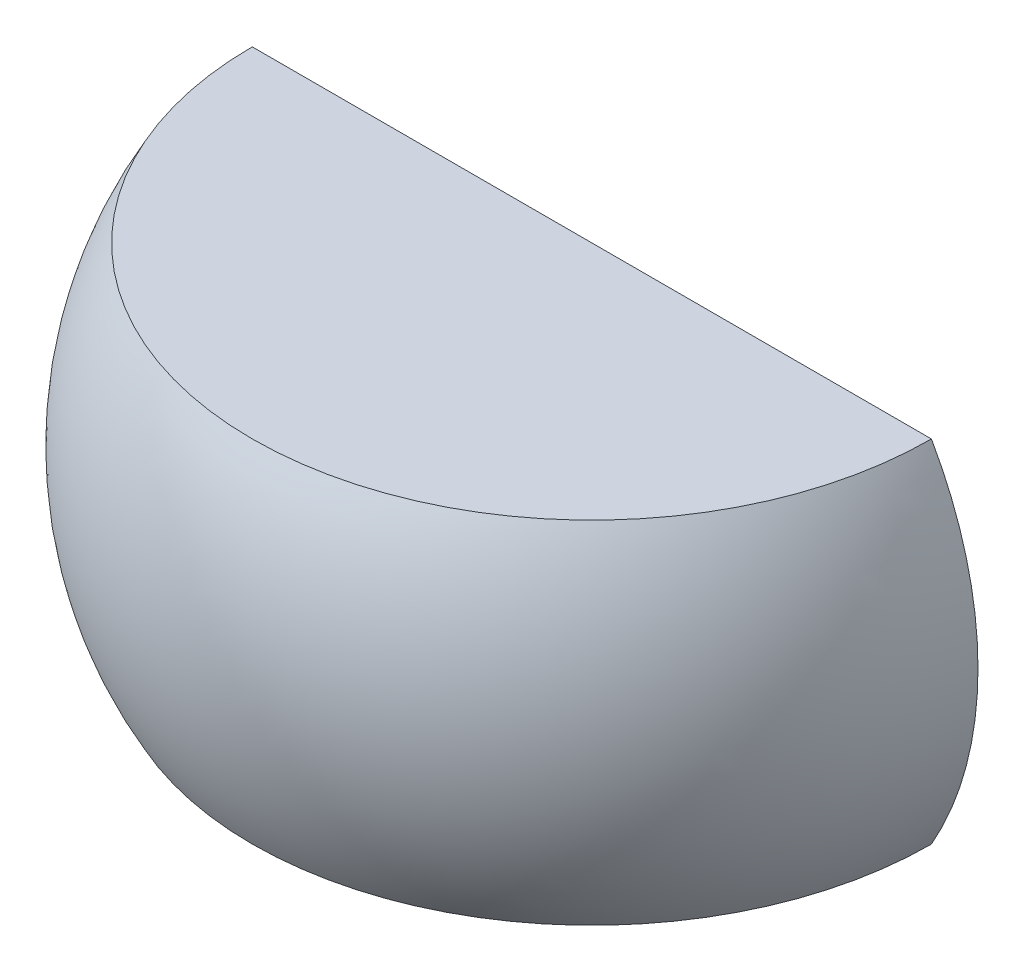
SolidWorks part; units mm, degrees
ref_plane "Alzado" through (0, 0, 0) normal (0, 0, 1) x (1, 0, 0)
ref_plane "Planta" through (0, 0, 0) normal (0, 1, 0) x (1, 0, 0)
ref_plane "Vista lateral" through (0, 0, 0) normal (1, 0, 0) x (0, 0, -1)
sketch "Croquis1" plane through (0, 0, 0) normal (0, 0, 1) x (1, 0, 0)
  line L0 (-51.7822, -4.3826) -> (-31.5822, -4.3826)
  line L1 (-51.7822, 17.4162) -> (-29.2822, 17.4162)
  line L2 (-53.2822, -5.8826) -> (-43.2485, -5.8826)
  line L3 (-31.5822, -4.3826) -> (-31.5822, -19.9667)
  line L5 (-36.7985, -13.9562) -> (-31.5822, -19.9667)
  line L6 (-43.2485, -5.8826) -> (-36.7985, -5.8826)
  line L8 (-36.7985, -5.8826) -> (-36.7985, -13.9562)
  line L9 (-29.2822, 18.9162) -> (-53.2822, 18.9162)
  line L10 (-29.2822, 17.4162) -> (-29.2822, 18.9162)
  arc A0 (-51.7822, 17.4162) -> (-51.7822, -4.3826) centre (-29.2832, 6.5168) ccw
  arc A1 (-53.2822, -5.8826) -> (-53.2822, 18.9162) centre (-31.5737, 6.5168) cw
  dimension "D3" = 1.5
  dimension "D4" = 25
  dimension "D2" = 22.5
  dimension "D5" = 1.5
revolve "Revolución1" add sketch "Croquis1" angle 180 about L10
sketch "Croquis2" plane through (0, 0, 0) normal (0, 0, -1) x (-1, 0, 0)
  line L0 (26.9822, -19.9667) -> (26.9822, -4.3826) construction
  line L1 (23.9822, -5.8826) -> (25.9822, -5.8826)
  line L2 (23.9822, -5.8826) -> (23.9822, -8.8826)
  line L3 (23.9822, -8.8826) -> (25.9822, -8.8826)
  line L4 (25.9822, -5.8826) -> (25.9822, -8.8826)
  line L6 (31.5822, -19.9667) -> (31.5822, -4.3826) construction
  line L11 (32.5822, -5.8826) -> (34.5822, -5.8826)
  line L12 (32.5822, -5.8826) -> (32.5822, -8.8826)
  line L13 (32.5822, -8.8826) -> (34.5822, -8.8826)
  line L14 (34.5822, -5.8826) -> (34.5822, -8.8826)
  line L15 (32.5822, -9.8826) -> (34.5822, -9.8826)
  line L16 (32.5822, -9.8826) -> (32.5822, -12.8826)
  line L17 (32.5822, -12.8826) -> (34.5822, -12.8826)
  line L18 (34.5822, -9.8826) -> (34.5822, -12.8826)
  line L19 (23.9822, -9.8826) -> (25.9822, -9.8826)
  line L20 (23.9822, -9.8826) -> (23.9822, -12.8826)
  line L21 (23.9822, -12.8826) -> (25.9822, -12.8826)
  line L22 (25.9822, -9.8826) -> (25.9822, -12.8826)
  dimension "D1" = 2
  dimension "D2" = 1
  dimension "D3" = 1
  dimension "D5" = 2
  dimension "D6" = 2
extrude "Cortar-Extruir1" cut sketch "Croquis2" against normal blind 15
sketch "Croquis3" plane through (-32.5822, 0, 0) normal (-1, 0, 0) x (0, 0, 1)
  line L0 (6.7532, -12.8826) -> (0, -12.8826) construction
  line L1 (4.7831, -12.8826) -> (11.8594, -12.8826)
  line L2 (4.7831, -12.8826) -> (4.7831, -9.8826)
  line L3 (4.7831, -9.8826) -> (11.8594, -9.8826)
  line L4 (11.8594, -12.8826) -> (11.8594, -9.8826)
  line L5 (6.7532, -8.8826) -> (0, -8.8826) construction
  line L6 (4.7831, -8.8826) -> (11.472, -8.8826)
  line L7 (4.7831, -8.8826) -> (4.7831, -5.8826)
  line L8 (4.7831, -5.8826) -> (11.472, -5.8826)
  line L9 (11.472, -8.8826) -> (11.472, -5.8826)
extrude "Cortar-Extruir2" cut sketch "Croquis3" against normal up to vertex
